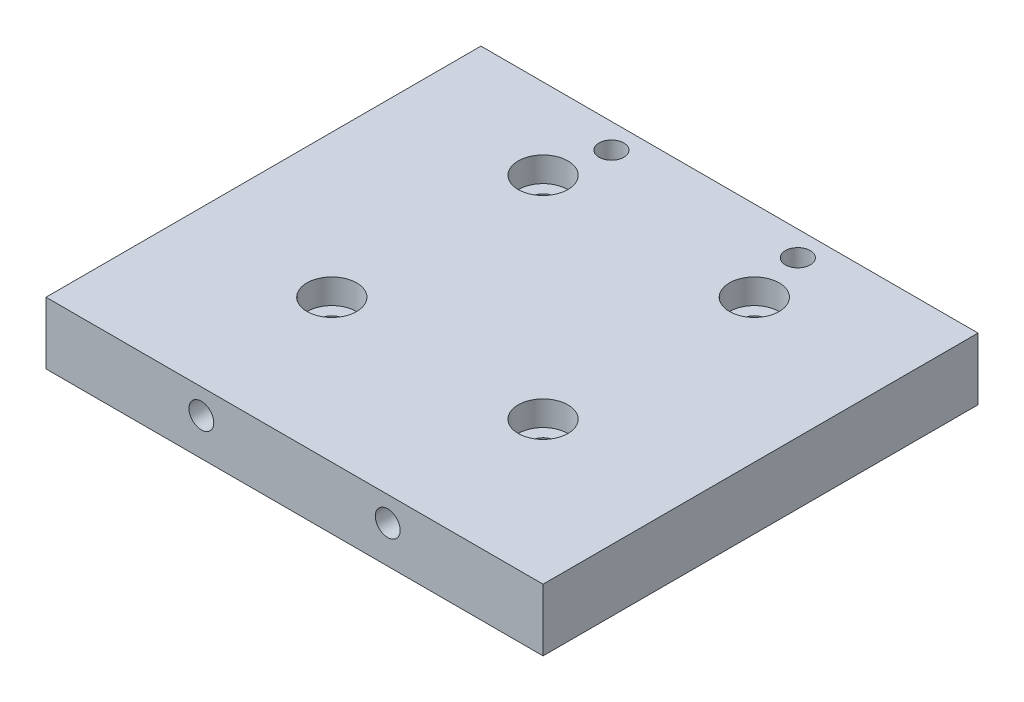
SolidWorks part; units mm, degrees
ref_plane "Front Plane" through (0, 0, 0) normal (0, 0, 1) x (1, 0, 0)
ref_plane "Top Plane" through (0, 0, 0) normal (0, 1, 0) x (1, 0, 0)
ref_plane "Right Plane" through (0, 0, 0) normal (1, 0, 0) x (0, 0, -1)
sketch "Sketch2" plane through (0, 0, 0) normal (0, 1, 0) x (1, 0, 0)
  line L0 (-8.5, 8.5) -> (8.5, 8.5) construction
  line L1 (-20, 15) -> (20, 15)
  line L2 (-20, 15) -> (-20, -15)
  line L3 (-20, -15) -> (20, -15)
  line L4 (20, 15) -> (20, -15)
  line L5 (-20, 15) -> (20, -15) construction
  line L6 (-20, -15) -> (20, 15) construction
  line L7 (0, 15) -> (0, -15) construction
  line L8 (-8.5, 8.5) -> (-8.5, -8.5) construction
  line L9 (-20, 0) -> (20, 0) construction
  circle A0 centre (-8.5, 8.5) radius 1
  circle A1 centre (8.5, 8.5) radius 1
  circle A2 centre (8.5, -8.5) radius 1
  circle A3 centre (-8.5, -8.5) radius 1
  point P0 (0, 0)
  point P16 (0, 8.5)
  point P19 (-8.5, 0)
  dimension "D3" = 2
  dimension "D4" = 2
  dimension "D5" = 2
  dimension "D6" = 2
  dimension "D1" = 30
  dimension "D2" = 40
  dimension "D7" = 17
  dimension "D8" = 17
extrude "Boss-Extrude1" add sketch "Sketch2" along normal blind 5
sketch "Sketch3" plane through (0, 5, 0) normal (0, 1, 0) x (1, 0, 0)
  circle A0 centre (-8.5, 8.5) radius 2
  circle A1 centre (8.5, 8.5) radius 2
  circle A2 centre (8.5, -8.5) radius 2
  circle A3 centre (-8.5, -8.5) radius 2
  dimension "D1" = 4
  dimension "D2" = 4
  dimension "D3" = 4
  dimension "D4" = 4
extrude "Cut-Extrude1" cut sketch "Sketch3" against normal blind 2
sketch "Sketch5" plane through (0, 0, 0) normal (0, -1, 0) x (1, 0, 0)
  line L0 (-7.5, -13) -> (7.5, -13) construction
  line L1 (20, -15) -> (-20, -15) construction
  line L2 (0, -15) -> (0, 15) construction
  line L3 (-20, 15) -> (20, 15) construction
  circle A0 centre (-7.5, -13) radius 1
  circle A1 centre (7.5, -13) radius 1
  point P10 (0, -13)
  dimension "D2" = 2
  dimension "D3" = 2
  dimension "D1" = 15
  dimension "D4" = 2
extrude "Cut-Extrude2" cut sketch "Sketch5" against normal through all
sketch "Sketch7" plane through (0, 0, 15) normal (0, 0, 1) x (1, 0, 0)
  line L1 (-20, 5) -> (20, 5)
  line L2 (-20, 5) -> (-20, 0)
  line L3 (-20, 0) -> (20, 0)
  line L4 (20, 5) -> (20, 0)
extrude "Boss-Extrude2" add sketch "Sketch7" along normal blind 5
sketch "Sketch8" plane through (0, 0, 20) normal (0, 0, 1) x (1, 0, 0)
  line L0 (-20, 0) -> (20, 0) construction
  line L1 (0, 5) -> (0, 0) construction
  line L2 (20, 5) -> (-20, 5) construction
  line L3 (-7.5, 3) -> (7.5, 3) construction
  circle A0 centre (-7.5, 3) radius 1
  circle A1 centre (7.5, 3) radius 1
  point P7 (0, 3)
  dimension "D3" = 2
  dimension "D4" = 2
  dimension "D1" = 15
  dimension "D2" = 3
extrude "Cut-Extrude3" cut sketch "Sketch8" against normal blind 5
